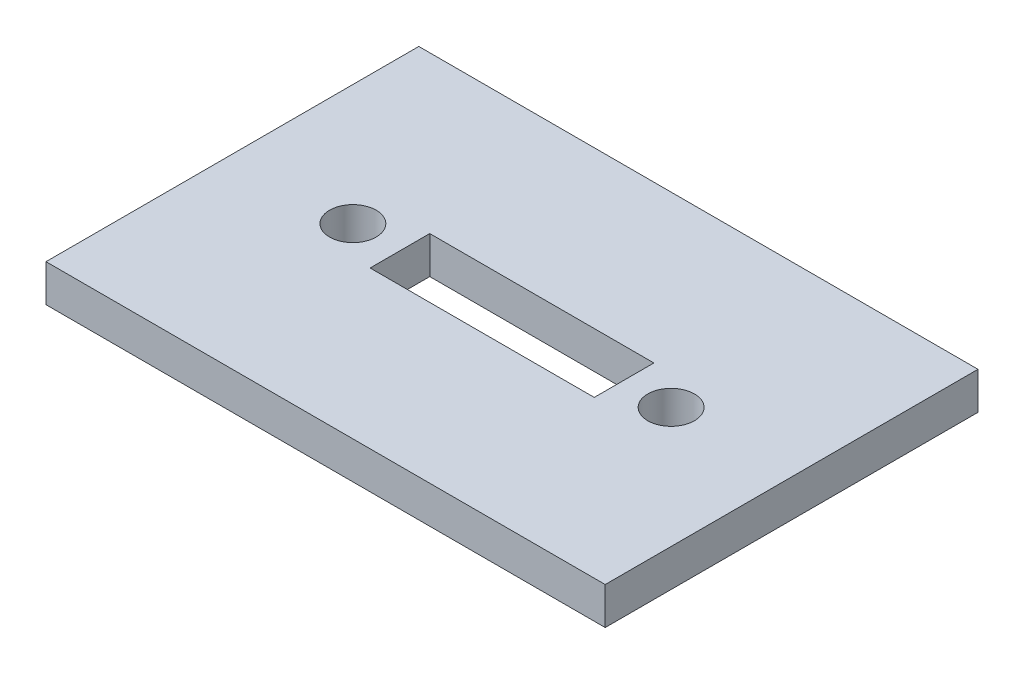
SolidWorks part; units mm, degrees
material "Copper"
ref_plane "Front Plane" through (0, 0, 0) normal (0, 0, 1) x (1, 0, 0)
ref_plane "Top Plane" through (0, 0, 0) normal (0, 1, 0) x (1, 0, 0)
ref_plane "Right Plane" through (0, 0, 0) normal (1, 0, 0) x (0, 0, -1)
sketch "Sketch1" plane through (0, 0, 0) normal (0, 1, 0) x (1, 0, 0)
  line L1 (0, 0) -> (4.7625, 0)
  line L2 (0, 0) -> (0, -3.175)
  line L3 (0, -3.175) -> (4.7625, -3.175)
  line L4 (4.7625, 0) -> (4.7625, -3.175)
  dimension "D1" = 3.175
  dimension "D2" = 4.7625
extrude "Boss-Extrude1" add sketch "Sketch1" along normal blind 0.3175
sketch "Sketch2" plane through (0, 0.3175, 0) normal (0, 1, 0) x (1, 0, 0)
  line L0 (0, -3.175) -> (2.3812, -3.175)
  line L1 (0, -3.175) -> (4.7625, -3.175) construction
  line L2 (0, -3.175) -> (0, -1.5875)
  line L3 (0, 0) -> (0, -3.175) construction
  line L4 (0, -1.5875) -> (2.3812, -1.5875)
sketch "Sketch3" plane through (0, 0.3175, 0) normal (0, 1, 0) x (1, 0, 0)
  line L0 (2.3812, -1.5875) -> (1.0262, -1.5875)
  line L1 (0, -1.5875) -> (2.3812, -1.5875) construction
  dimension "D1" = 1.3551
hole_wizard "1/64 (0.01563) Diameter Hole1" positions "Sketch4" profile "Sketch5" hole size "1/64" standard "ANSI Inch"
sketch "Sketch4" plane through (0, 0.3175, 0) normal (0, 1, 0) x (1, 0, 0)
  point P0 (1.0262, -1.5875)
sketch "Sketch5" plane through (1.0262, 0.3175, 1.5875) normal (1, 0, 0) x (0, 0, 1)
  line L0 (0, 0) -> (0, 6.5166)
  line L1 (0, 6.5166) -> (0.1985, 6.35)
  line L2 (0.1985, 6.35) -> (0.1985, 0)
  line L5 (0.1985, 0) -> (0, 0)
  line L10 (0, 6.5166) -> (-0.1985, 6.35) construction
  line L11 (0, -6.35) -> (0, 107.95) construction
  dimension "Hole Dia." = 0.397
  dimension "Hole Depth" = 6.35
  dimension "Drill Angle" = 100
sketch "Sketch6" plane through (0, 0.3175, 0) normal (0, 1, 0) x (1, 0, 0)
  line L0 (2.3812, -1.5875) -> (3.7363, -1.5875)
  dimension "D1" = 1.3551
hole_wizard "1/64 (0.01563) Diameter Hole2" positions "Sketch7" profile "Sketch8" hole size "1/64" standard "ANSI Inch"
sketch "Sketch7" plane through (0, 0.3175, 0) normal (0, 1, 0) x (1, 0, 0)
  point P0 (3.7363, -1.5875)
sketch "Sketch8" plane through (3.7363, 0.3175, 1.5875) normal (1, 0, 0) x (0, 0, 1)
  line L0 (0, 0) -> (0, 6.5166)
  line L1 (0, 6.5166) -> (0.1985, 6.35)
  line L2 (0.1985, 6.35) -> (0.1985, 0)
  line L5 (0.1985, 0) -> (0, 0)
  line L10 (0, 6.5166) -> (-0.1985, 6.35) construction
  line L11 (0, -6.35) -> (0, 107.95) construction
  dimension "Hole Dia." = 0.397
  dimension "Hole Depth" = 6.35
  dimension "Drill Angle" = 100
sketch "Sketch9" plane through (0, 0.3175, 0) normal (0, 1, 0) x (1, 0, 0)
  line L1 (3.3357, -1.8415) -> (1.4268, -1.8415)
  line L2 (3.3357, -1.8415) -> (3.3357, -1.3335)
  line L3 (3.3357, -1.3335) -> (1.4268, -1.3335)
  line L4 (1.4268, -1.8415) -> (1.4268, -1.3335)
  line L5 (3.3357, -1.8415) -> (1.4268, -1.3335) construction
  line L6 (3.3357, -1.3335) -> (1.4268, -1.8415) construction
  point P0 (2.3812, -1.5875)
  dimension "D1" = 0.508
extrude "Cut-Extrude1" cut sketch "Sketch9" against normal through all
